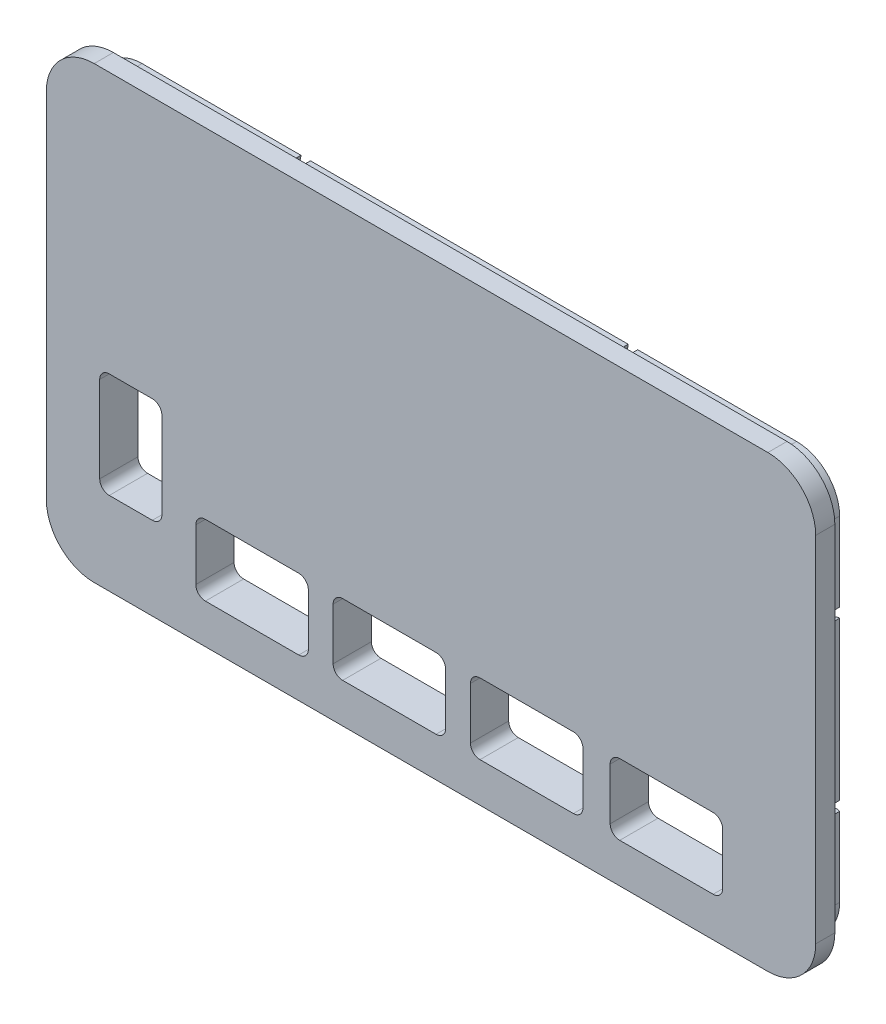
SolidWorks part; units mm, degrees
ref_plane "前视基准面" through (0, 0, 0) normal (0, 0, 1) x (1, 0, 0)
ref_plane "上视基准面" through (0, 0, 0) normal (0, 1, 0) x (1, 0, 0)
ref_plane "右视基准面" through (0, 0, 0) normal (1, 0, 0) x (0, 0, -1)
other "Configuration Table"
ref_plane "基准面1" through (0, 0, 994.7617) normal (0, 0, 1) x (1, 0, 0)
sketch "草图1" plane through (0, 0, 994.7617) normal (0, 0, 1) x (1, 0, 0)
  line L4 (-36.9772, -23.153) -> (-20.3758, -23.153)
  line L5 (35.9285, -18.653) -> (35.9285, -10.4094)
  line L6 (31.4285, 20.8216) -> (14.8271, 20.8216)
  line L7 (-41.4772, 16.3216) -> (-41.4772, 8.078)
  line L8 (-36.9772, -23.153) -> (-20.3758, -23.153)
  line L9 (35.9285, -18.653) -> (35.9285, -10.4094)
  line L10 (31.4285, 20.8216) -> (14.8271, 20.8216)
  line L11 (-41.4772, 16.3216) -> (-41.4772, 8.078)
  line L84 (35.9285, 8.078) -> (35.9285, 16.3216)
  line L85 (35.9285, 8.078) -> (35.9285, 16.3216)
  line L86 (-20.3758, 20.8216) -> (-36.9772, 20.8216)
  line L87 (-20.3758, 20.8216) -> (-36.9772, 20.8216)
  line L88 (-41.4772, -10.4094) -> (-41.4772, -18.653)
  line L89 (-41.4772, -10.4094) -> (-41.4772, -18.653)
  line L90 (14.8271, -23.153) -> (31.4285, -23.153)
  line L91 (14.8271, -23.153) -> (31.4285, -23.153)
  line L92 (15.3271, 19.8216) -> (13.3271, 19.8216)
  line L93 (15.3271, 19.8216) -> (13.3271, 19.8216)
  line L94 (13.8271, 20.8216) -> (-19.3758, 20.8216)
  line L95 (13.8271, 20.8216) -> (-19.3758, 20.8216)
  line L96 (-18.8758, 19.8216) -> (-20.8758, 19.8216)
  line L97 (-18.8758, 19.8216) -> (-20.8758, 19.8216)
  line L98 (-40.6203, 8.578) -> (-40.6203, 6.578)
  line L99 (-40.6203, 8.578) -> (-40.6203, 6.578)
  line L100 (-41.4772, 7.078) -> (-41.4772, -9.4094)
  line L101 (-41.4772, 7.078) -> (-41.4772, -9.4094)
  line L102 (-40.6203, -8.9094) -> (-40.6203, -10.9094)
  line L103 (-40.6203, -8.9094) -> (-40.6203, -10.9094)
  line L104 (-20.8758, -22.153) -> (-18.8758, -22.153)
  line L105 (-20.8758, -22.153) -> (-18.8758, -22.153)
  line L106 (-19.3758, -23.153) -> (13.8271, -23.153)
  line L107 (-19.3758, -23.153) -> (13.8271, -23.153)
  line L108 (13.3271, -22.153) -> (15.3271, -22.153)
  line L109 (13.3271, -22.153) -> (15.3271, -22.153)
  line L110 (35.0716, -10.9094) -> (35.0716, -8.9094)
  line L111 (35.0716, -10.9094) -> (35.0716, -8.9094)
  line L112 (35.9285, -9.4094) -> (35.9285, 7.078)
  line L113 (35.9285, -9.4094) -> (35.9285, 7.078)
  line L114 (35.0716, 6.578) -> (35.0716, 8.578)
  line L115 (35.0716, 6.578) -> (35.0716, 8.578)
  arc A4 (-41.4772, -18.653) -> (-36.9772, -23.153) centre (-36.9772, -18.653) ccw
  arc A5 (31.4285, -23.153) -> (35.9285, -18.653) centre (31.4285, -18.653) ccw
  arc A6 (35.9285, 16.3216) -> (31.4285, 20.8216) centre (31.4285, 16.3216) ccw
  arc A7 (-36.9772, 20.8216) -> (-41.4772, 16.3216) centre (-36.9772, 16.3216) ccw
  arc A8 (-41.4772, -18.653) -> (-36.9772, -23.153) centre (-36.9772, -18.653) ccw
  arc A9 (31.4285, -23.153) -> (35.9285, -18.653) centre (31.4285, -18.653) ccw
  arc A10 (35.9285, 16.3216) -> (31.4285, 20.8216) centre (31.4285, 16.3216) ccw
  arc A11 (-36.9772, 20.8216) -> (-41.4772, 16.3216) centre (-36.9772, 16.3216) ccw
  arc A84 (14.8271, 20.8216) -> (15.3271, 19.8216) centre (16.0771, 20.8216) ccw
  arc A85 (14.8271, 20.8216) -> (15.3271, 19.8216) centre (16.0771, 20.8216) ccw
  arc A86 (13.3271, 19.8216) -> (13.8271, 20.8216) centre (12.5771, 20.8216) ccw
  arc A87 (13.3271, 19.8216) -> (13.8271, 20.8216) centre (12.5771, 20.8216) ccw
  arc A88 (-19.3758, 20.8216) -> (-18.8758, 19.8216) centre (-18.1258, 20.8216) ccw
  arc A89 (-19.3758, 20.8216) -> (-18.8758, 19.8216) centre (-18.1258, 20.8216) ccw
  arc A90 (-20.8758, 19.8216) -> (-20.3758, 20.8216) centre (-21.6258, 20.8216) ccw
  arc A91 (-20.8758, 19.8216) -> (-20.3758, 20.8216) centre (-21.6258, 20.8216) ccw
  arc A92 (-41.4772, 8.078) -> (-40.6203, 8.578) centre (-41.1946, 8.578) ccw
  arc A93 (-41.4772, 8.078) -> (-40.6203, 8.578) centre (-41.1946, 8.578) ccw
  arc A94 (-40.6203, 6.578) -> (-41.4772, 7.078) centre (-41.4772, 6.0937) ccw
  arc A95 (-40.6203, 6.578) -> (-41.4772, 7.078) centre (-41.4772, 6.0937) ccw
  arc A96 (-41.4772, -9.4094) -> (-40.6203, -8.9094) centre (-41.4772, -8.4251) ccw
  arc A97 (-41.4772, -9.4094) -> (-40.6203, -8.9094) centre (-41.4772, -8.4251) ccw
  arc A98 (-40.6203, -10.9094) -> (-41.4772, -10.4094) centre (-41.1946, -10.9094) ccw
  arc A99 (-40.6203, -10.9094) -> (-41.4772, -10.4094) centre (-41.1946, -10.9094) ccw
  arc A100 (-20.3758, -23.153) -> (-20.8758, -22.153) centre (-21.6258, -23.153) ccw
  arc A101 (-20.3758, -23.153) -> (-20.8758, -22.153) centre (-21.6258, -23.153) ccw
  arc A102 (-18.8758, -22.153) -> (-19.3758, -23.153) centre (-18.1258, -23.153) ccw
  arc A103 (-18.8758, -22.153) -> (-19.3758, -23.153) centre (-18.1258, -23.153) ccw
  arc A104 (13.8271, -23.153) -> (13.3271, -22.153) centre (12.5771, -23.153) ccw
  arc A105 (13.8271, -23.153) -> (13.3271, -22.153) centre (12.5771, -23.153) ccw
  arc A106 (15.3271, -22.153) -> (14.8271, -23.153) centre (16.0771, -23.153) ccw
  arc A107 (15.3271, -22.153) -> (14.8271, -23.153) centre (16.0771, -23.153) ccw
  arc A108 (35.9285, -10.4094) -> (35.0716, -10.9094) centre (35.6459, -10.9094) ccw
  arc A109 (35.9285, -10.4094) -> (35.0716, -10.9094) centre (35.6459, -10.9094) ccw
  arc A110 (35.0716, -8.9094) -> (35.9285, -9.4094) centre (35.9285, -8.4251) ccw
  arc A111 (35.0716, -8.9094) -> (35.9285, -9.4094) centre (35.9285, -8.4251) ccw
  arc A112 (35.9285, 7.078) -> (35.0716, 6.578) centre (35.9285, 6.0937) ccw
  arc A113 (35.9285, 7.078) -> (35.0716, 6.578) centre (35.9285, 6.0937) ccw
  arc A114 (35.0716, 8.578) -> (35.9285, 8.078) centre (35.6459, 8.578) ccw
  arc A115 (35.0716, 8.578) -> (35.9285, 8.078) centre (35.6459, 8.578) ccw
  dimension "D1" = 0
extrude "凸台-拉伸1" add sketch "草图1" along normal blind 2
sketch "草图2" plane through (0, 0, 996.7617) normal (0, 0, 1) x (1, 0, 0)
  line L4 (-42.9772, 17.3216) -> (-42.9772, -19.653)
  line L5 (-37.9772, -24.653) -> (32.4285, -24.653)
  line L6 (37.4285, -19.653) -> (37.4285, 17.3216)
  line L7 (32.4285, 22.3216) -> (-37.9772, 22.3216)
  line L8 (-42.9772, 17.3216) -> (-42.9772, -19.653)
  line L9 (-37.9772, -24.653) -> (32.4285, -24.653)
  line L10 (37.4285, -19.653) -> (37.4285, 17.3216)
  line L11 (32.4285, 22.3216) -> (-37.9772, 22.3216)
  arc A4 (-37.9772, 22.3216) -> (-42.9772, 17.3216) centre (-37.9772, 17.3216) ccw
  arc A5 (-42.9772, -19.653) -> (-37.9772, -24.653) centre (-37.9772, -19.653) ccw
  arc A6 (32.4285, -24.653) -> (37.4285, -19.653) centre (32.4285, -19.653) ccw
  arc A7 (37.4285, 17.3216) -> (32.4285, 22.3216) centre (32.4285, 17.3216) ccw
  arc A8 (-37.9772, 22.3216) -> (-42.9772, 17.3216) centre (-37.9772, 17.3216) ccw
  arc A9 (-42.9772, -19.653) -> (-37.9772, -24.653) centre (-37.9772, -19.653) ccw
  arc A10 (32.4285, -24.653) -> (37.4285, -19.653) centre (32.4285, -19.653) ccw
  arc A11 (37.4285, 17.3216) -> (32.4285, 22.3216) centre (32.4285, 17.3216) ccw
  dimension "D1" = 0
extrude "凸台-拉伸2" add sketch "草图2" along normal blind 2
sketch "草图3" plane through (0, 0, 998.7617) normal (0, 0, 1) x (1, 0, 0)
  line L0 (-24.4898, -20.5208) -> (-18.4699, -20.5208)
  line L1 (-10.1388, -20.5208) -> (-4.1188, -20.5208)
  line L2 (4.2123, -20.5208) -> (10.2322, -20.5208)
  line L3 (18.8173, -20.5208) -> (24.8372, -20.5208)
  line L12 (-37.403, -4.9787) -> (-37.403, -15.9787)
  line L13 (-37.403, -15.9787) -> (-30.903, -15.9787)
  line L14 (-30.903, -15.9787) -> (-30.903, -4.9787)
  line L15 (-30.903, -4.9787) -> (-37.403, -4.9787)
  line L16 (-37.403, -5.9787) -> (-37.403, -14.9787)
  line L17 (-36.403, -15.9787) -> (-31.903, -15.9787)
  line L18 (-30.903, -14.9787) -> (-30.903, -5.9787)
  line L19 (-31.903, -4.9787) -> (-36.403, -4.9787)
  line L40 (-18.4699, -20.5208) -> (-16.5999, -20.5208)
  line L41 (-15.5999, -19.5208) -> (-15.5999, -14.1209)
  line L42 (-16.5999, -13.1209) -> (-26.3598, -13.1209)
  line L43 (-27.3598, -14.1209) -> (-27.3598, -19.5208)
  line L44 (-26.3598, -20.5208) -> (-24.4898, -20.5208)
  line L64 (-4.1188, -20.5208) -> (-2.2489, -20.5208)
  line L65 (-1.2489, -19.5208) -> (-1.2489, -14.1209)
  line L66 (-2.2489, -13.1209) -> (-12.0088, -13.1209)
  line L67 (-13.0088, -14.1209) -> (-13.0088, -19.5208)
  line L68 (-12.0088, -20.5208) -> (-10.1388, -20.5208)
  line L88 (10.2322, -20.5208) -> (12.1022, -20.5208)
  line L89 (13.1022, -19.5208) -> (13.1022, -14.1209)
  line L90 (12.1022, -13.1209) -> (2.3423, -13.1209)
  line L91 (1.3423, -14.1209) -> (1.3423, -19.5208)
  line L92 (2.3423, -20.5208) -> (4.2123, -20.5208)
  line L112 (24.8372, -20.5208) -> (26.7072, -20.5208)
  line L113 (27.7072, -19.5208) -> (27.7072, -14.1209)
  line L114 (26.7072, -13.1209) -> (16.9473, -13.1209)
  line L115 (15.9473, -14.1209) -> (15.9473, -19.5208)
  line L116 (16.9473, -20.5208) -> (18.8173, -20.5208)
  arc A4 (26.7072, -20.5208) -> (27.7072, -19.5208) centre (26.7072, -19.5208) ccw
  arc A5 (27.7072, -14.1209) -> (26.7072, -13.1209) centre (26.7072, -14.1209) ccw
  arc A6 (16.9473, -20.5208) -> (15.9473, -19.5208) centre (16.9473, -19.5208) cw
  arc A7 (16.9473, -13.1209) -> (15.9473, -14.1209) centre (16.9473, -14.1209) ccw
  arc A8 (13.1022, -14.1209) -> (12.1022, -13.1209) centre (12.1022, -14.1209) ccw
  arc A9 (12.1022, -20.5208) -> (13.1022, -19.5208) centre (12.1022, -19.5208) ccw
  arc A10 (1.3423, -19.5208) -> (2.3423, -20.5208) centre (2.3423, -19.5208) ccw
  arc A11 (1.3423, -14.1209) -> (2.3423, -13.1209) centre (2.3423, -14.1209) cw
  arc A12 (-1.2489, -14.1209) -> (-2.2489, -13.1209) centre (-2.2489, -14.1209) ccw
  arc A13 (-1.2489, -19.5208) -> (-2.2489, -20.5208) centre (-2.2489, -19.5208) cw
  arc A14 (-12.0088, -20.5208) -> (-13.0088, -19.5208) centre (-12.0088, -19.5208) cw
  arc A15 (-12.0088, -13.1209) -> (-13.0088, -14.1209) centre (-12.0088, -14.1209) ccw
  arc A16 (-16.5999, -20.5208) -> (-15.5999, -19.5208) centre (-16.5999, -19.5208) ccw
  arc A17 (-26.3598, -20.5208) -> (-27.3598, -19.5208) centre (-26.3598, -19.5208) cw
  arc A18 (-15.5999, -14.1209) -> (-16.5999, -13.1209) centre (-16.5999, -14.1209) ccw
  arc A19 (-27.3598, -14.1209) -> (-26.3598, -13.1209) centre (-26.3598, -14.1209) cw
  arc A20 (-31.903, -15.9787) -> (-30.903, -14.9787) centre (-31.903, -14.9787) ccw
  arc A21 (-36.403, -15.9787) -> (-37.403, -14.9787) centre (-36.403, -14.9787) cw
  arc A22 (-30.903, -5.9787) -> (-31.903, -4.9787) centre (-31.903, -5.9787) ccw
  arc A23 (-36.403, -4.9787) -> (-37.403, -5.9787) centre (-36.403, -5.9787) ccw
  dimension "D6" = 1
  dimension "D1" = 0.5
extrude "切除-拉伸1" cut sketch "草图3" against normal blind 5
